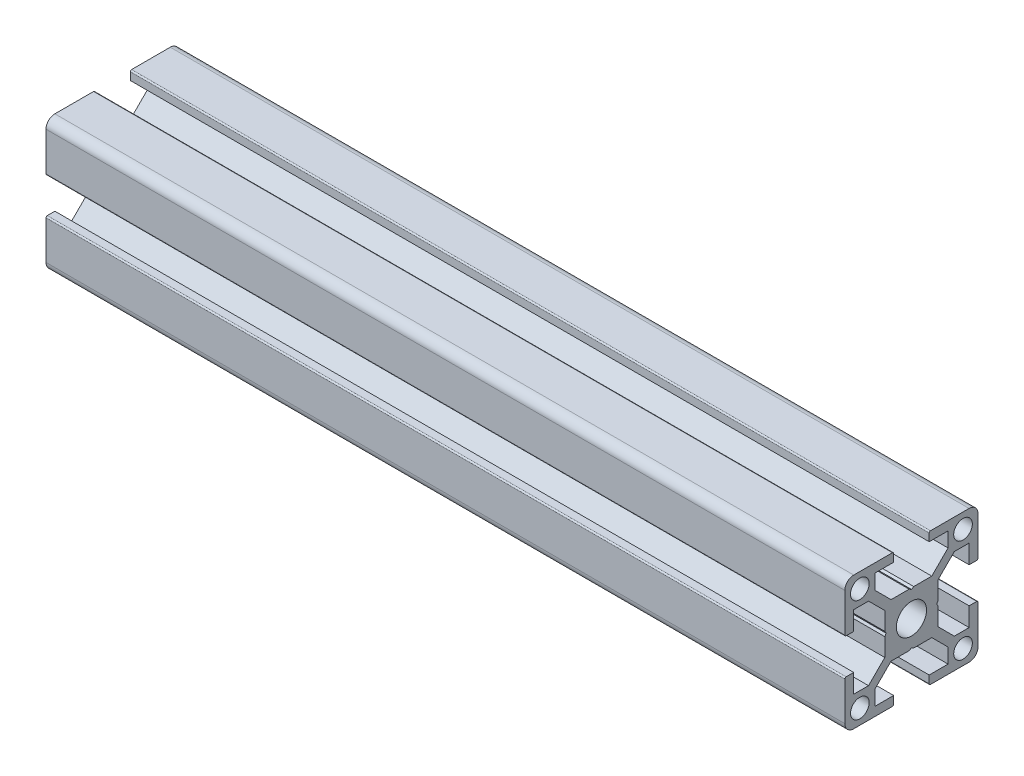
SolidWorks part; units mm, degrees
ref_plane "Front Plane" through (0, 0, 0) normal (0, 0, 1) x (1, 0, 0)
ref_plane "Top Plane" through (0, 0, 0) normal (0, 1, 0) x (1, 0, 0)
ref_plane "Right Plane" through (0, 0, 0) normal (1, 0, 0) x (0, 0, -1)
sketch "Sketch1" plane through (0, 0, 0) normal (0, 0, 1) x (1, 0, 0)
  line L0 (0, 0) -> (180, 0)
  dimension "D1" = 180
other "30xs6 30X30S6(1)"
ref_plane "Plane1" through (0, 0, 0) normal (1, 0, 0) x (0, 1, 0)
sketch "草图1" plane through (0, 0, 0) normal (1, 0, 0) x (0, 1, 0)
  line L0 (-14.7, 4) -> (-13, 4)
  line L1 (-13, 4) -> (-13, 8.25)
  line L2 (-13, 8.25) -> (-9.6642, 8.25)
  line L3 (-9.6642, 8.25) -> (-6, 4.5858)
  line L4 (-6, 4.5858) -> (-6, 0.5196)
  line L5 (-6, 0.5196) -> (-5.7, 0)
  line L6 (-5.7, 0) -> (-6, -0.5196)
  line L7 (-6, -0.5196) -> (-6, -4.5858)
  line L8 (-6, -4.5858) -> (-9.6642, -8.25)
  line L9 (-9.6642, -8.25) -> (-13, -8.25)
  line L10 (-13, -8.25) -> (-13, -4)
  line L11 (-13, -4) -> (-14.7, -4)
  line L12 (-15, -4.3) -> (-15, -13)
  line L13 (-13, -15) -> (-4.3, -15)
  line L14 (-4, -14.7) -> (-4, -13)
  line L15 (-4, -13) -> (-8.25, -13)
  line L16 (-8.25, -13) -> (-8.25, -9.6642)
  line L17 (-8.25, -9.6642) -> (-4.5858, -6)
  line L18 (-4.5858, -6) -> (-0.5196, -6)
  line L19 (-0.5196, -6) -> (0, -5.7)
  line L20 (0, -5.7) -> (0.5196, -6)
  line L21 (0.5196, -6) -> (4.5858, -6)
  line L22 (4.5858, -6) -> (8.25, -9.6642)
  line L23 (8.25, -9.6642) -> (8.25, -13)
  line L24 (8.25, -13) -> (4, -13)
  line L25 (4, -13) -> (4, -14.7)
  line L26 (4.3, -15) -> (13, -15)
  line L27 (15, -13) -> (15, -4.3)
  line L28 (14.7, -4) -> (13, -4)
  line L29 (13, -4) -> (13, -8.25)
  line L30 (13, -8.25) -> (9.6642, -8.25)
  line L31 (9.6642, -8.25) -> (6, -4.5858)
  line L32 (6, -4.5858) -> (6, -0.5196)
  line L33 (6, -0.5196) -> (5.7, 0)
  line L34 (5.7, 0) -> (6, 0.5196)
  line L35 (6, 0.5196) -> (6, 4.5858)
  line L36 (6, 4.5858) -> (9.6642, 8.25)
  line L37 (9.6642, 8.25) -> (13, 8.25)
  line L38 (13, 8.25) -> (13, 4)
  line L39 (13, 4) -> (14.7, 4)
  line L40 (15, 4.3) -> (15, 13)
  line L41 (13, 15) -> (4.3, 15)
  line L42 (4, 14.7) -> (4, 13)
  line L43 (4, 13) -> (8.25, 13)
  line L44 (8.25, 13) -> (8.25, 9.6642)
  line L45 (8.25, 9.6642) -> (4.5858, 6)
  line L46 (4.5858, 6) -> (0.5196, 6)
  line L47 (0.5196, 6) -> (0, 5.7)
  line L48 (0, 5.7) -> (-0.5196, 6)
  line L49 (-0.5196, 6) -> (-4.5858, 6)
  line L50 (-4.5858, 6) -> (-8.25, 9.6642)
  line L51 (-8.25, 9.6642) -> (-8.25, 13)
  line L52 (-8.25, 13) -> (-4, 13)
  line L53 (-4, 13) -> (-4, 14.7)
  line L54 (-4.3, 15) -> (-13, 15)
  line L55 (-15, 13) -> (-15, 4.3)
  arc A0 (-15, 4.3) -> (-14.7, 4) centre (-14.7, 4.3) ccw
  arc A1 (-14.7, -4) -> (-15, -4.3) centre (-14.7, -4.3) ccw
  arc A2 (-15, -13) -> (-13, -15) centre (-13, -13) ccw
  arc A3 (-4.3, -15) -> (-4, -14.7) centre (-4.3, -14.7) ccw
  arc A4 (4, -14.7) -> (4.3, -15) centre (4.3, -14.7) ccw
  arc A5 (13, -15) -> (15, -13) centre (13, -13) ccw
  arc A6 (15, -4.3) -> (14.7, -4) centre (14.7, -4.3) ccw
  arc A7 (14.7, 4) -> (15, 4.3) centre (14.7, 4.3) ccw
  arc A8 (15, 13) -> (13, 15) centre (13, 13) ccw
  arc A9 (4.3, 15) -> (4, 14.7) centre (4.3, 14.7) ccw
  arc A10 (-4, 14.7) -> (-4.3, 15) centre (-4.3, 14.7) ccw
  arc A11 (-13, 15) -> (-15, 13) centre (-13, 13) ccw
  circle A12 centre (11.625, 11.625) radius 2.1
  circle A13 centre (11.625, -11.625) radius 2.1
  circle A14 centre (0, 0) radius 3.4
  circle A15 centre (-11.625, -11.625) radius 2.1
  circle A16 centre (-11.625, 11.625) radius 2.1
  point P90 (-15, 15)
  point P91 (-0.2598, 14.9121)
  point P92 (15, 15)
  point P93 (15, 0)
  point P94 (15, -15)
  point P95 (0.2598, -15)
  point P96 (-15, -15)
  point P97 (-15, 0)
  point P98 (0, 0)
